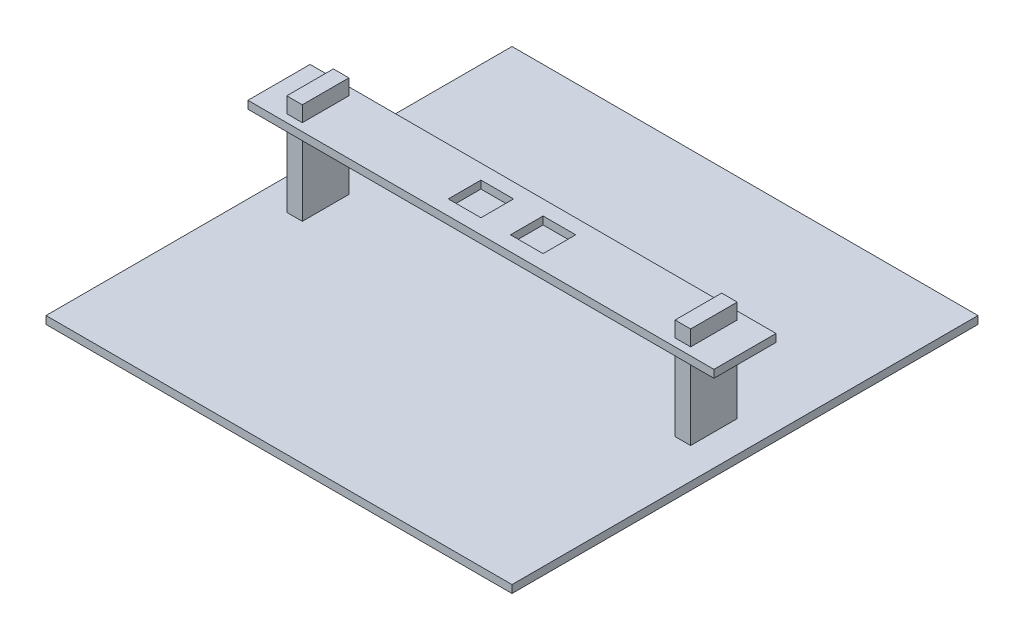
SolidWorks part; units mm, degrees
ref_plane "Front Plane" through (0, 0, 0) normal (0, 0, 1) x (1, 0, 0)
ref_plane "Top Plane" through (0, 0, 0) normal (0, 1, 0) x (1, 0, 0)
ref_plane "Right Plane" through (0, 0, 0) normal (1, 0, 0) x (0, 0, -1)
sketch "Sketch1" plane through (0, 0, 0) normal (0, 1, 0) x (1, 0, 0)
  line L1 (-300, 300) -> (300, 300)
  line L2 (-300, 300) -> (-300, -300)
  line L3 (-300, -300) -> (300, -300)
  line L4 (300, 300) -> (300, -300)
  line L5 (-300, 300) -> (300, -300) construction
  line L6 (-300, -300) -> (300, 300) construction
  point P0 (0, 0)
  dimension "D1" = 300
  dimension "D2" = 300
extrude "Boss-Extrude1" add sketch "Sketch1" along normal blind 10
sketch "Sketch2" plane through (0, 10, 0) normal (0, 1, 0) x (1, 0, 0)
  line L0 (-300, 0) -> (300, 0) construction
  line L1 (-300, 300) -> (-300, -300) construction
  line L2 (300, -300) -> (300, 300) construction
  line L3 (0, 300) -> (0, -300) construction
  line L4 (-61, -21) -> (-19, -21)
  line L5 (-61, -21) -> (-61, 21)
  line L6 (-61, 21) -> (-19, 21)
  line L7 (-19, -21) -> (-19, 21)
  line L8 (-61, -21) -> (-19, 21) construction
  line L9 (-61, 21) -> (-19, -21) construction
  line L10 (300, 300) -> (-300, 300) construction
  line L11 (-300, -300) -> (300, -300) construction
  line L12 (61, 21) -> (19, 21)
  line L13 (19, -21) -> (19, 21)
  line L14 (61, -21) -> (19, -21)
  line L15 (61, -21) -> (61, 21)
  line L16 (260, -30) -> (240, -30)
  line L17 (-260, 30) -> (-240, 30)
  line L18 (-260, 30) -> (-260, -30)
  line L19 (-260, -30) -> (-240, -30)
  line L20 (-240, 30) -> (-240, -30)
  line L21 (-260, 30) -> (-240, -30) construction
  line L22 (-260, -30) -> (-240, 30) construction
  line L23 (240, 30) -> (240, -30)
  line L24 (260, 30) -> (240, 30)
  line L25 (260, 30) -> (260, -30)
  point P6 (-40, 0)
  point P22 (-250, 0)
  dimension "D1" = 42
  dimension "D2" = 40
  dimension "D3" = 250
  dimension "D4" = 60
  dimension "D5" = 20
extrude "Boss-Extrude2" add sketch "Sketch2" along normal blind 130 contours L20 L17 L18 L19 | L25 L24 L23 L16
ref_plane "Plane1" through (0, 110, 0) normal (0, 1, 0) x (1, 0, 0)
sketch "Sketch3" plane through (0, 110, 0) normal (0, 1, 0) x (1, 0, 0)
  line L0 (-240, -30) -> (-240, 30) construction
  line L1 (-240, 30) -> (-260, 30) construction
  line L2 (-260, 30) -> (-260, -30) construction
  line L3 (-260, -30) -> (-240, -30) construction
  line L4 (300, -300) -> (300, 300)
  line L5 (300, 300) -> (-300, 300)
  line L6 (-300, 300) -> (-300, -300)
  line L7 (-300, -300) -> (300, -300)
  line L8 (300, -300) -> (300, 300)
  line L9 (300, 300) -> (-300, 300)
  line L10 (-300, 300) -> (-300, -300)
  line L11 (-300, -300) -> (300, -300)
  line L12 (260, -30) -> (260, 30) construction
  line L13 (260, 30) -> (240, 30) construction
  line L14 (240, 30) -> (240, -30) construction
  line L15 (240, -30) -> (260, -30) construction
  line L16 (-240, -30) -> (-240, 30)
  line L17 (-240, 30) -> (-260, 30)
  line L18 (-260, 30) -> (-260, -30)
  line L19 (-260, -30) -> (-240, -30)
  line L20 (260, -30) -> (260, 30)
  line L21 (260, 30) -> (240, 30)
  line L22 (240, 30) -> (240, -30)
  line L23 (240, -30) -> (260, -30)
  dimension "D1" = 0
extrude "Boss-Extrude3" add sketch "Sketch3" along normal blind 10
sketch "Sketch4" plane through (0, 120, 0) normal (0, 1, 0) x (1, 0, 0)
  line L0 (-300, 0) -> (300, 0) construction
  line L1 (-300, 300) -> (-300, -300) construction
  line L2 (300, -300) -> (300, 300) construction
  line L4 (-300, 40) -> (300, 40)
  line L5 (-300, 40) -> (-300, -40)
  line L6 (-300, -40) -> (300, -40)
  line L7 (300, 40) -> (300, -40)
  point P10 (300, 0)
  dimension "D1" = 80
extrude "Cut-Extrude1" cut sketch "Sketch4" against normal blind 10 flip side to cut
sketch "Sketch5" plane through (0, 120, 0) normal (0, 1, 0) x (1, 0, 0)
  line L4 (-61, -21) -> (-19, -21)
  line L5 (-19, -21) -> (-19, 21)
  line L6 (-19, 21) -> (-61, 21)
  line L7 (-61, 21) -> (-61, -21)
  line L8 (-61, -21) -> (-19, -21)
  line L9 (-19, -21) -> (-19, 21)
  line L10 (-19, 21) -> (-61, 21)
  line L11 (-61, 21) -> (-61, -21)
  line L28 (61, 21) -> (19, 21)
  line L29 (19, 21) -> (19, -21)
  line L30 (19, -21) -> (61, -21)
  line L31 (61, -21) -> (61, 21)
  line L32 (61, 21) -> (19, 21)
  line L33 (19, 21) -> (19, -21)
  line L34 (19, -21) -> (61, -21)
  line L35 (61, -21) -> (61, 21)
  dimension "D1" = 0
  dimension "D4" = 0
extrude "Cut-Extrude2" cut sketch "Sketch5" against normal blind 10
